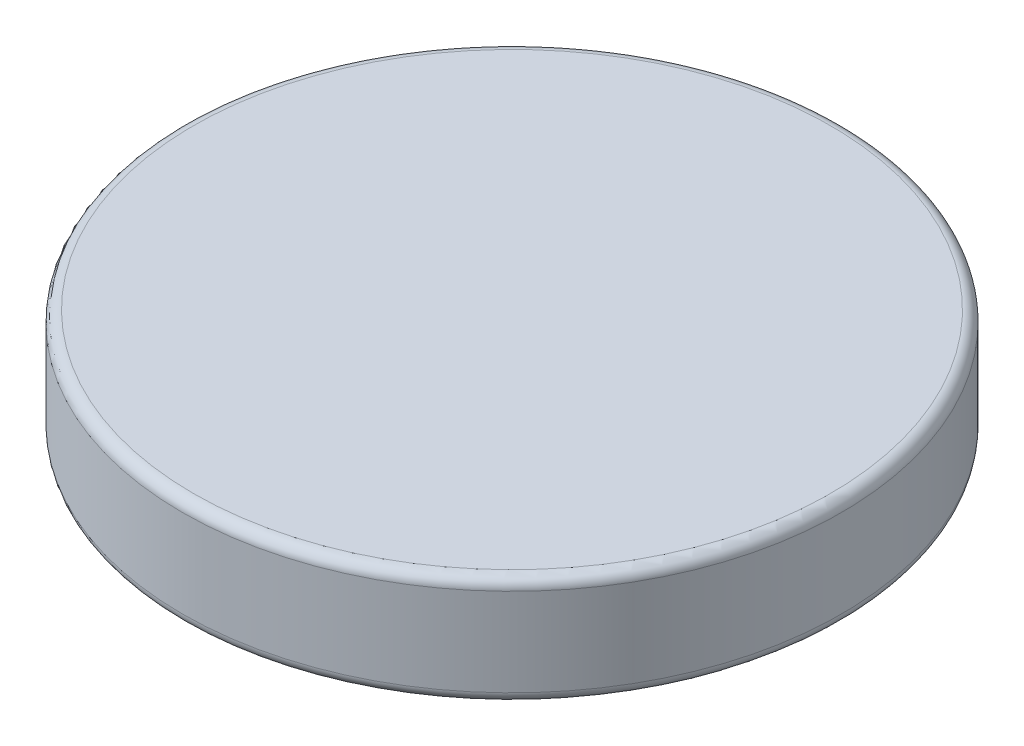
SolidWorks part; units mm, degrees
ref_plane "前视基准面" through (0, 0, 0) normal (0, 0, 1) x (1, 0, 0)
ref_plane "上视基准面" through (0, 0, 0) normal (0, 1, 0) x (1, 0, 0)
ref_plane "右视基准面" through (0, 0, 0) normal (1, 0, 0) x (0, 0, -1)
sketch "草图1" plane through (0, 0, 0) normal (0, 1, 0) x (1, 0, 0)
  circle A0 centre (0, 0) radius 6
  dimension "D1" = 12
extrude "凸台-拉伸1" add sketch "草图1" along normal blind 2
fillet "圆角1" radius 0.2 2 edges at (0, 2, 6) (0, 0, 6)
